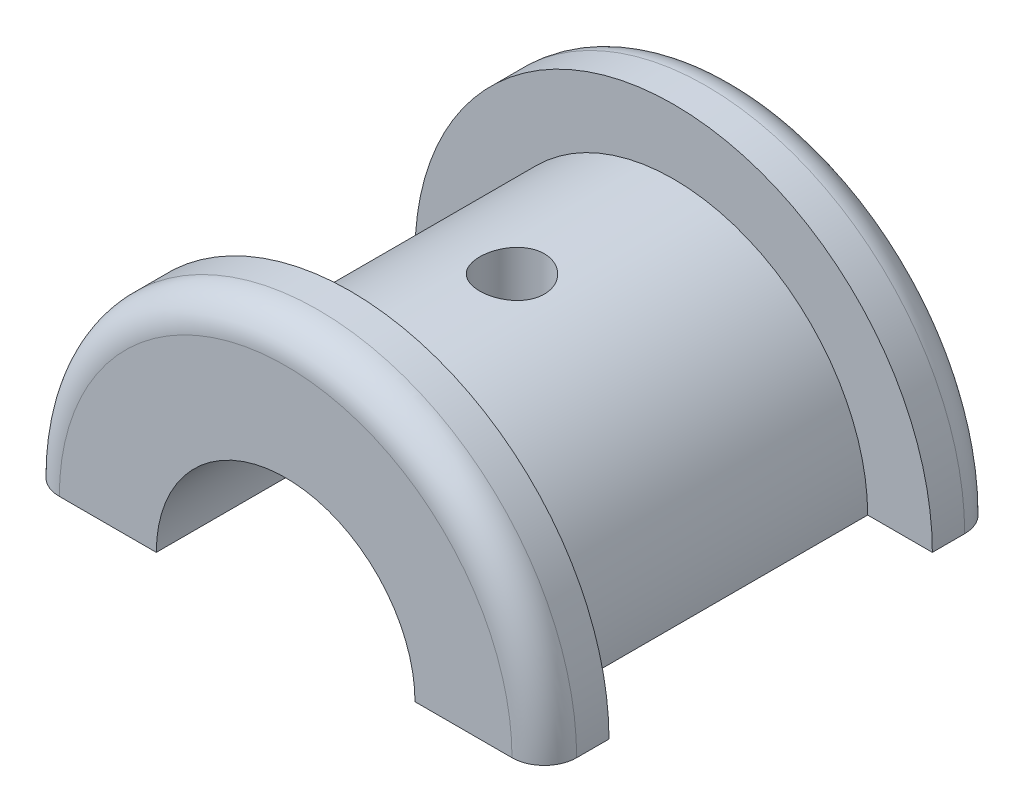
SolidWorks part; units mm, degrees
ref_plane "Front Plane" through (0, 0, 0) normal (0, 0, 1) x (1, 0, 0)
ref_plane "Top Plane" through (0, 0, 0) normal (0, 1, 0) x (1, 0, 0)
ref_plane "Right Plane" through (0, 0, 0) normal (1, 0, 0) x (0, 0, -1)
sketch "Sketch1" plane through (0, 0, 0) normal (0, 0, 1) x (1, 0, 0)
  line L0 (-8, 0) -> (-4, 0)
  line L1 (4, 0) -> (8, 0)
  arc A0 (-8, 0) -> (8, 0) centre (0, 0) cw
  arc A1 (-4, 0) -> (4, 0) centre (0, 0) cw
  dimension "D1" = 8
  dimension "D2" = 4
extrude "Boss-Extrude1" add sketch "Sketch1" along normal mid plane 14
sketch "Sketch2" plane through (0, 0, 0) normal (0, 0, 1) x (1, 0, 0)
  line L0 (-8, 0) -> (-4, 0) construction
  line L1 (4, 0) -> (8, 0) construction
  line L2 (-8, 0) -> (-6, 0)
  line L3 (6, 0) -> (8, 0)
  arc A0 (-6, 0) -> (6, 0) centre (0, 0) cw
  arc A1 (8, 0) -> (-8, 0) centre (0, 0) ccw construction
  arc A2 (8, 0) -> (-8, 0) centre (0, 0) ccw
  dimension "D1" = 6
extrude "Cut-Extrude1" cut sketch "Sketch2" against normal mid plane 10
fillet "Fillet1" radius 1 2 edges at (0, 8, -7) (0, 8, 7)
sketch "Sketch3" plane through (0, 0, 0) normal (0, 1, 0) x (1, 0, 0)
  circle A0 centre (0, 0) radius 1
  dimension "D1" = 2
extrude "Cut-Extrude2" cut sketch "Sketch3" along normal through all
